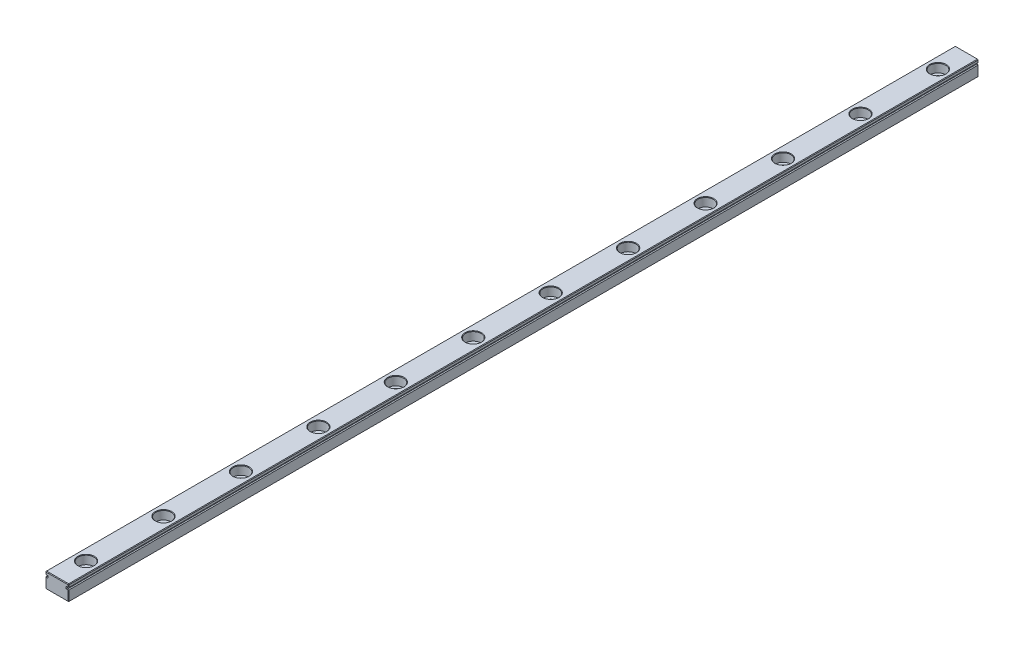
SolidWorks part; units mm, degrees
material "AISI 304"
ref_plane "Front Plane" through (0, 0, 0) normal (0, 0, 1) x (1, 0, 0)
ref_plane "Top Plane" through (0, 0, 0) normal (0, 1, 0) x (1, 0, 0)
ref_plane "Right Plane" through (0, 0, 0) normal (1, 0, 0) x (0, 0, -1)
sketch "Sketch1" plane through (0, 0, 0) normal (0, 0, 1) x (1, 0, 0)
  line L0 (0, 0) -> (0, 8) construction
  line L1 (0, 8) -> (12, 8)
  line L2 (0, 0) -> (12, 0)
  line L3 (0, 8) -> (0, 6.75)
  line L4 (0, 6.75) -> (0.5, 6.25) construction
  line L5 (0.5, 6.25) -> (1, 6.25)
  line L6 (0.5, 5.75) -> (0, 5.25) construction
  line L7 (0, 5.25) -> (0, 0)
  line L8 (1, 6.25) -> (1, 5.75)
  line L9 (1, 5.75) -> (0.5, 5.75)
  line L10 (0.5, 5.75) -> (0.75, 6) construction
  line L11 (0.75, 6) -> (0.5, 6.25) construction
  line L12 (0, 6.75) -> (0, 6.559)
  line L13 (0, 5.25) -> (0, 5.441)
  line L14 (6, 8) -> (6, 0) construction
  line L15 (11.25, 6) -> (11.5, 6.25) construction
  line L16 (11.5, 5.75) -> (11.25, 6) construction
  line L17 (11.5, 5.75) -> (12, 5.25) construction
  line L18 (12, 6.75) -> (11.5, 6.25) construction
  line L19 (12, 0) -> (12, 8) construction
  line L20 (12, 5.25) -> (12, 5.441)
  line L21 (12, 6.75) -> (12, 6.559)
  line L22 (11, 5.75) -> (11.5, 5.75)
  line L23 (11, 6.25) -> (11, 5.75)
  line L24 (12, 5.25) -> (12, 0)
  line L25 (11.5, 6.25) -> (11, 6.25)
  line L26 (12, 8) -> (12, 6.75)
  arc A0 (0, 5.441) -> (0.5, 5.75) centre (0, 6) ccw
  arc A1 (0.5, 6.25) -> (0, 6.559) centre (0, 6) ccw
  arc A2 (11.5, 6.25) -> (12, 6.559) centre (12, 6) cw
  arc A3 (12, 5.441) -> (11.5, 5.75) centre (12, 6) cw
  point P4 (1, 6)
  point P28 (11, 6)
  dimension "D1" = 8
  dimension "D2" = 6
  dimension "D3" = 0.5
  dimension "D4" = 45
  dimension "D5" = 2
  dimension "D6" = 1
extrude "Boss-Extrude1" add sketch "Sketch1" along normal blind 470
chamfer "Chamfer1" distance 0.3 angle 45 36 edges at (0, 0, 235) (12, 0, 235) (0, 8, 235) (12, 8, 235) (0.2939, 5.5245, 470) (0.75, 5.75, 470) (1, 6, 470) (0.75, 6.25, 470) (0.2939, 6.4755, 470) (0, 7.2795, 470) (6, 8, 470) (12, 7.2795, 470) (11.7061, 6.4755, 470) (11.25, 6.25, 470) (11, 6, 470) (11.25, 5.75, 470) (11.7061, 5.5245, 470) (12, 2.7205, 470) (6, 0, 470) (0, 2.7205, 470) (12, 2.7205, 0) (11.7061, 5.5245, 0) (11.25, 5.75, 0) (11, 6, 0) (11.25, 6.25, 0) (11.7061, 6.4755, 0) (12, 7.2795, 0) (6, 0, 0) (0, 2.7205, 0) (0.2939, 5.5245, 0) (0.75, 5.75, 0) (1, 6, 0) (0.75, 6.25, 0) (0.2939, 6.4755, 0) (0, 7.2795, 0) (6, 8, 0)
hole_wizard "CBORE for M5 Hex Head Bolt1" positions "3DSketch1" profile "Sketch3" counterbore size "M5" standard "ANSI Metric" end condition through all
sketch3d "3DSketch1"
  line L0 (6, 8, 0) -> (6, 8, 15) construction
  line L1 (11.7, 8, 0) -> (0.3, 8, 0) construction
  point P0 (6, 8, 15)
  dimension "D1" = 15
sketch "Sketch3" plane through (6, 8, 15) normal (1, 0, 0) x (0, 0, 1)
  line L0 (0, 0) -> (0, 8)
  line L1 (2.25, 7.75) -> (2.5, 8)
  line L2 (4, 4.5) -> (2.25, 4.5)
  line L3 (2.25, 4.5) -> (2.25, 7.75)
  line L5 (4, 4.5) -> (4, 0.25)
  line L6 (4, 0.25) -> (4.25, 0)
  line L7 (4.25, 0) -> (0, 0)
  line L8 (-4, 0.25) -> (-4.25, 0) construction
  line L11 (0, -6.35) -> (0, 107.95) construction
  line L12 (2.5, 8) -> (0, 8)
  line L13 (-2.25, 7.75) -> (-2.5, 8) construction
  dimension "Thru Hole Dia." = 4.5
  dimension "Thru Hole Depth" = 8
  dimension "C'Bore Dia." = 8
  dimension "C'Bore Depth" = 4.5
  dimension "Near C'Sink Dia." = 8.5
  dimension "Near C'Sink Angle" = 90
  dimension "Far C'Sink Dia." = 5
  dimension "Far C'Sink Angle" = 90
pattern_linear "LPattern1" count 12 spacing 40 along (0, 0, 1) of "CBORE for M5 Hex Head Bolt1"
